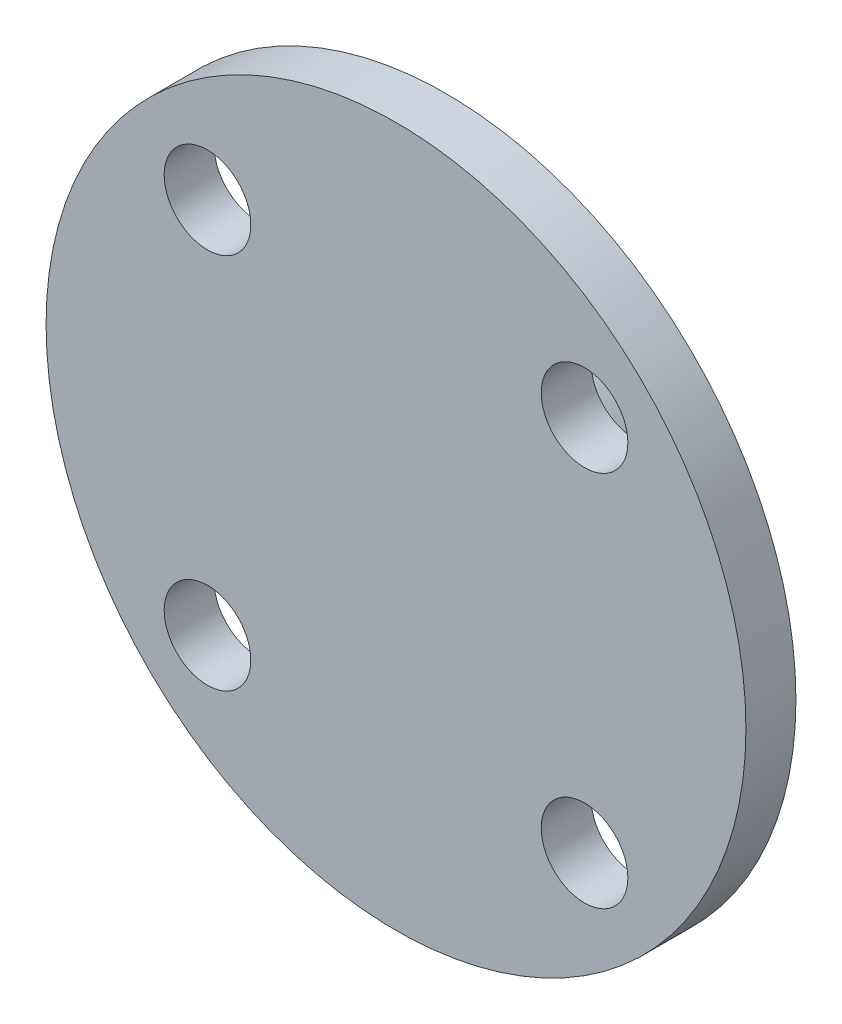
SolidWorks part; units mm, degrees
ref_plane "Спереди" through (0, 0, 0) normal (0, 0, 1) x (1, 0, 0)
ref_plane "Сверху" through (0, 0, 0) normal (0, 1, 0) x (1, 0, 0)
ref_plane "Справа" through (0, 0, 0) normal (1, 0, 0) x (0, 0, -1)
sketch "Эскиз1" plane through (0, 0, 0) normal (0, 1, 0) x (1, 0, 0)
  line L0 (0, 0) -> (-21, 0)
  line L1 (-21, 0) -> (-21, 3)
  line L2 (-21, 3) -> (-11, 3)
  line L3 (-11, 3) -> (-11, 7)
  line L4 (-11, 7) -> (0, 7)
  line L5 (0, 7) -> (0, 0)
  dimension "D1" = 21
  dimension "D2" = 11
  dimension "D3" = 7
  dimension "D4" = 3
revolve "Повернуть1" add sketch "Эскиз1" angle 360 about L5
sketch "Эскиз2" plane through (0, 0, 0) normal (0, 0, 1) x (1, 0, 0)
  line L0 (0, 0) -> (0, 21) construction
  circle A0 centre (11.3137, 11.3137) radius 2.6
  circle A1 centre (0, 0) radius 21 construction
  dimension "D1" = 5.2
  dimension "D2" = 16
  dimension "D3" = 45
extrude "Вырез-Вытянуть1" cut sketch "Эскиз2" against normal up to surface (3 mm away) up to face at (-21, 0, -3)
pattern_circular "Круговой массив1" count 4 over 360 about axis through (0, 0, 0) along (0, 0, 1) of "Вырез-Вытянуть1"
